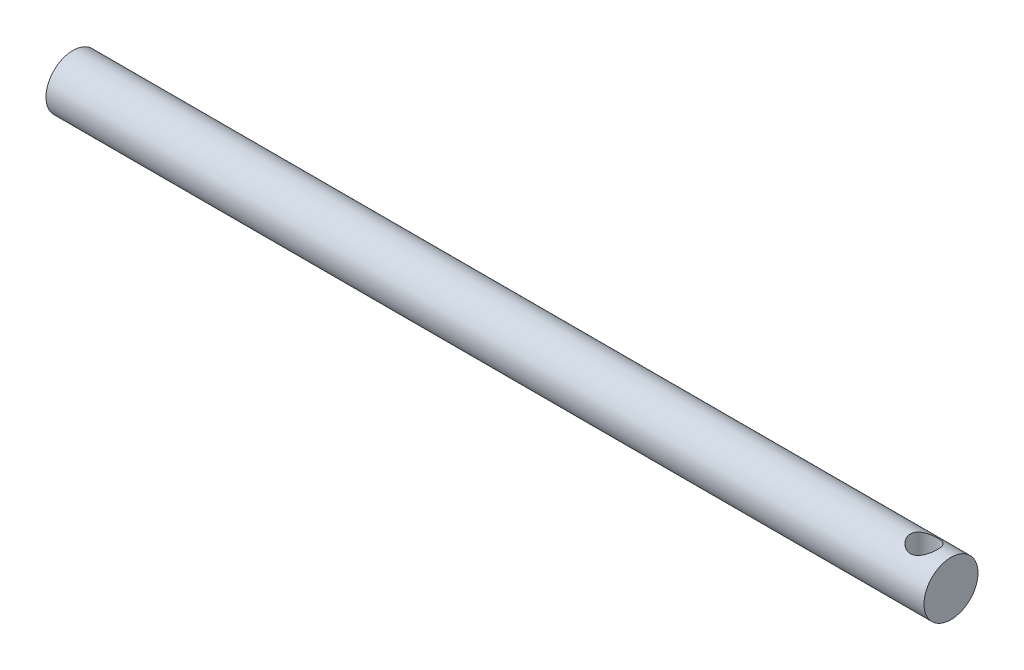
SolidWorks part; units mm, degrees
ref_plane "Alzado" through (0, 0, 0) normal (0, 0, 1) x (1, 0, 0)
ref_plane "Planta" through (0, 0, 0) normal (0, 1, 0) x (1, 0, 0)
ref_plane "Vista lateral" through (0, 0, 0) normal (1, 0, 0) x (0, 0, -1)
sketch "Croquis1" plane through (0, 0, 0) normal (1, 0, 0) x (0, 0, -1)
  circle A0 centre (0, 0) radius 10
extrude "Saliente-Extruir1" add sketch "Croquis1" along normal blind 325
sketch "Croquis3" plane through (0, 0, 0) normal (0, 1, 0) x (1, 0, 0)
  line L0 (325, 0) -> (315, 0) construction
  line L1 (325, -10) -> (325, 10) construction
  circle A0 centre (315, 0) radius 5
  dimension "D1" = 10
extrude "Cortar-Extruir1" cut sketch "Croquis3" against normal through all both and the other way through all contours A0
